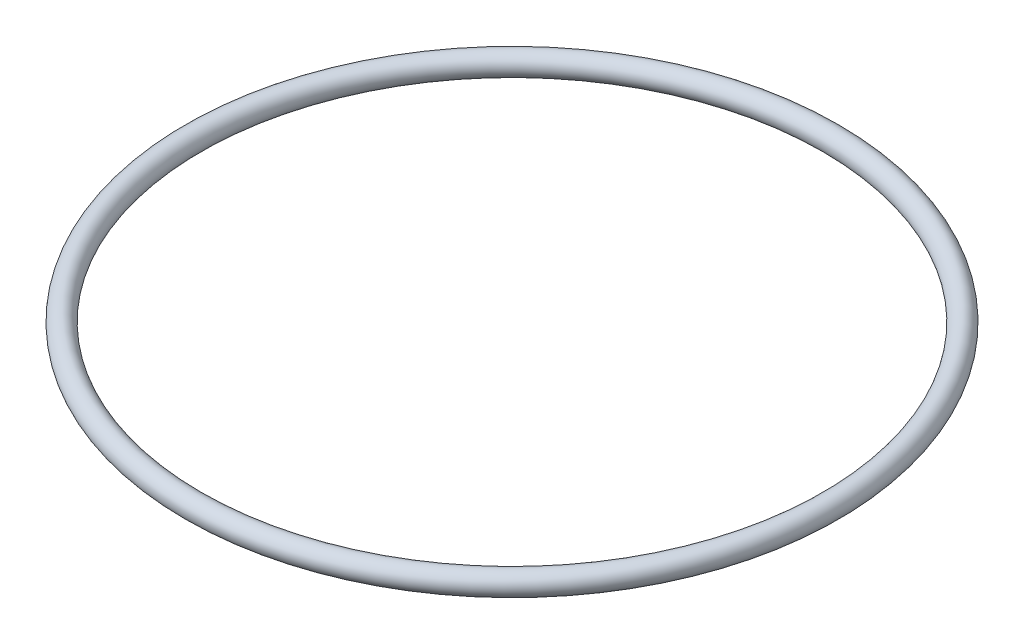
SolidWorks part; units mm, degrees
material "VITON"
ref_plane "Front Plane" through (0, 0, 0) normal (0, 0, 1) x (1, 0, 0)
ref_plane "Top Plane" through (0, 0, 0) normal (0, 1, 0) x (1, 0, 0)
ref_plane "Right Plane" through (0, 0, 0) normal (1, 0, 0) x (0, 0, -1)
sketch "Sketch1" plane through (0, 0, 0) normal (0, 0, 1) x (1, 0, 0)
  line L0 (0, 0) -> (0, -28.9993) construction
  circle A1 centre (50.9524, 0) radius 1.7653
  dimension "D1" = 3.5306
  dimension "D2" = 50.9524
revolve "Revolve1" add sketch "Sketch1" angle 360 about L0
